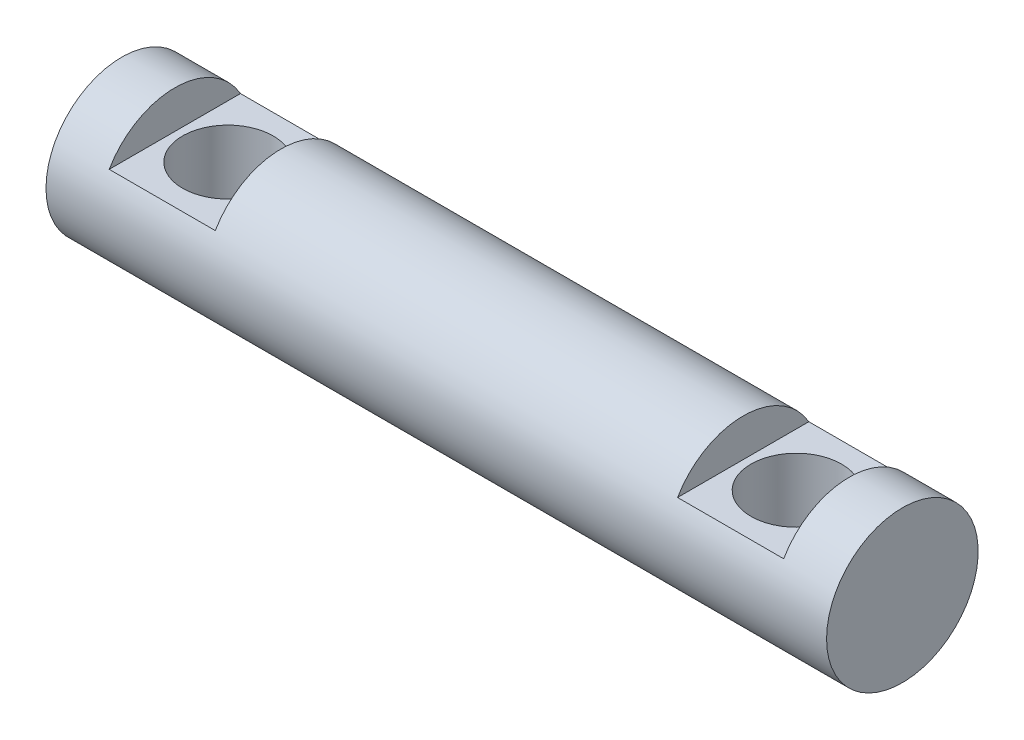
SolidWorks part; units mm, degrees
ref_plane "Plan de face" through (0, 0, 0) normal (0, 0, 1) x (1, 0, 0)
ref_plane "Plan de dessus" through (0, 0, 0) normal (0, 1, 0) x (1, 0, 0)
ref_plane "Plan de droite" through (0, 0, 0) normal (1, 0, 0) x (0, 0, -1)
sketch "Esquisse1" plane through (0, 0, 0) normal (0, 0, 1) x (1, 0, 0)
  line L0 (0, 0) -> (103, 0)
  line L1 (103, 0) -> (103, 10)
  line L2 (103, 10) -> (0, 10)
  line L3 (0, 10) -> (0, 0)
  dimension "D1" = 10
  dimension "D2" = 103
revolve "Révolution1" add sketch "Esquisse1" angle 360 about L0
sketch "Esquisse8" plane through (0, 0, 0) normal (0, 1, 0) x (1, 0, 0)
  line L0 (0, 0) -> (103, 0)
  line L1 (103, -10) -> (103, 10) construction
  line L2 (14, 10) -> (14, -10)
  line L3 (103, 10) -> (0, 10) construction
  line L4 (0, -10) -> (103, -10) construction
  line L5 (89, 10) -> (89, -10)
  line L6 (0, 10) -> (0, -10) construction
  circle A0 centre (14, 0) radius 5.983
  circle A1 centre (89, 0) radius 5.983
  dimension "D3" = 11.966
  dimension "D4" = 11.966
  dimension "D1" = 14
  dimension "D2" = 75
extrude "Enlèv. mat.-Extru.4" cut sketch "Esquisse8" against normal through all and the other way through all contours A0 | A1
sketch "Esquisse9" plane through (0, 0, 0) normal (0, 1, 0) x (1, 0, 0)
  line L0 (0, -10) -> (103, -10) construction
  line L1 (7, 10) -> (21, 10)
  line L2 (7, 10) -> (7, -10)
  line L3 (7, -10) -> (21, -10)
  line L4 (21, 10) -> (21, -10)
  line L5 (7, 10) -> (21, -10) construction
  line L6 (7, -10) -> (21, 10) construction
  line L7 (51.5, 16.0821) -> (51.5, -24.4122)
  line L8 (96, -10) -> (82, 10) construction
  line L9 (96, 10) -> (82, -10) construction
  line L10 (82, 10) -> (82, -10)
  line L11 (96, -10) -> (82, -10)
  line L12 (96, 10) -> (96, -10)
  line L13 (96, 10) -> (82, 10)
  point P0 (14, 0)
  point P14 (89, 0)
  dimension "D1" = 14
extrude "Enlèv. mat.-Extru.6" cut sketch "Esquisse9" along normal through all from offset 5 contours L1 L4 L3 L2 | L13 L10 L11 L12
